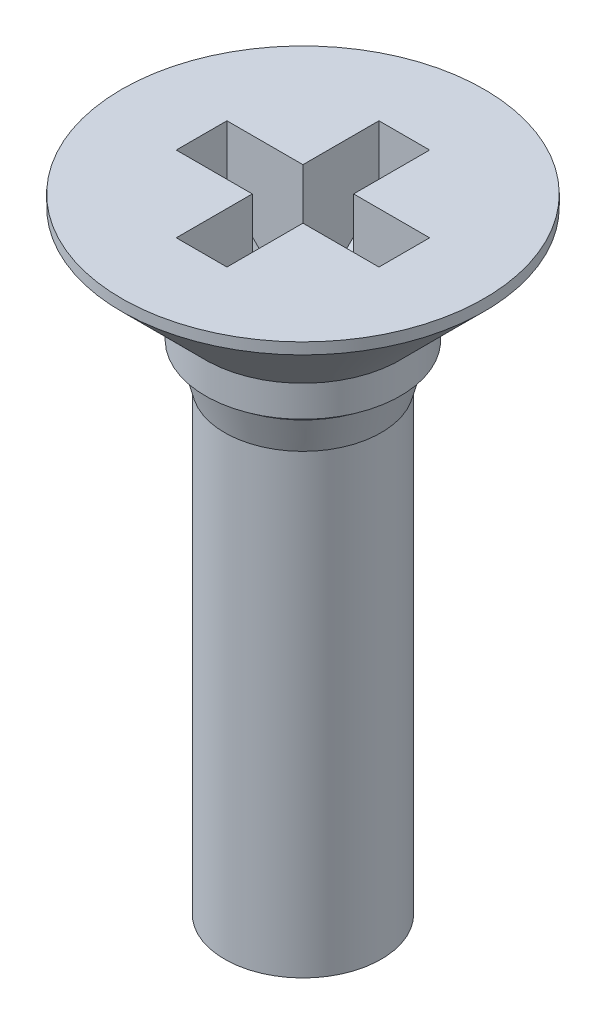
SolidWorks part; units mm, degrees
ref_plane "Vorderseite" through (0, 0, 0) normal (0, 0, 1) x (1, 0, 0)
ref_plane "Oben" through (0, 0, 0) normal (0, 1, 0) x (1, 0, 0)
ref_plane "Rechts" through (0, 0, 0) normal (1, 0, 0) x (0, 0, -1)
sketch "Skizze1" plane through (0, 0, 0) normal (0, 0, 1) x (1, 0, 0)
  line L0 (0, 0) -> (4.65, 0)
  line L1 (4.65, 0) -> (4.65, -0.29)
  line L2 (4.65, -0.29) -> (2.5, -2.44)
  line L3 (2.24, -3.24) -> (2.24, -3.4398)
  line L4 (2.24, -3.4398) -> (2.0095, -4.3)
  line L5 (2.0095, -4.3) -> (2.0095, -16)
  line L6 (2.0095, -16) -> (0, -16)
  line L7 (0, 0) -> (0, -16) construction
  line L8 (0, 0) -> (0, -16)
  line L10 (2.5, -2.44) -> (2.5, -3.24)
  line L12 (2.5, -3.24) -> (2.24, -3.24)
  point P3 (2.24, -2.7)
  dimension "D1" = 45
  dimension "D2" = 15
  dimension "K" = 2.7
  dimension "DA" = 9.3
  dimension "DK" = 4.019
  dimension "L" = 16
  dimension "DG" = 5
  dimension "A" = 1.6
  dimension "DF" = 4.48
  dimension "P" = 0.8
revolve "Basis-Rotation" add sketch "Skizze1" angle 360 about L7
sketch "Skizze2" plane through (0, 0, 0) normal (0, 0, 1) x (1, 0, 0)
  line L0 (0, -3.2) -> (0, 0) construction
  line L1 (0, 0) -> (0, -16) construction
  line L2 (-1, -3.2) -> (1, -3.2)
  line L3 (2.6, 0) -> (2.6, -1.6)
  line L4 (2.6, -1.6) -> (1, -3.2)
  line L5 (2.6, 0) -> (-2.6, 0)
  line L6 (-2.6, -1.6) -> (-1, -3.2)
  line L7 (-2.6, 0) -> (-2.6, -1.6)
  line L8 (0, -1.6) -> (2.6, -1.6) construction
  line L9 (4.65, 0) -> (-4.65, 0) construction
  line L11 (2.5, -2.44) -> (4.65, -0.29) construction
  point P11 (0, 0)
  dimension "M" = 5.2
  dimension "T" = 3.2
extrude "Kreuzschlitz1 H" cut sketch "Skizze2" against normal blind 0.65 and the other way blind 0.65
sketch "Skizze3" plane through (0, 0, 0) normal (1, 0, 0) x (0, 0, -1)
  line L0 (0, -3.2) -> (0, 0) construction
  line L2 (-1, -3.2) -> (1, -3.2)
  line L3 (2.6, 0) -> (2.6, -1.6)
  line L4 (2.6, -1.6) -> (1, -3.2)
  line L5 (2.6, 0) -> (-2.6, 0)
  line L6 (-2.6, -1.6) -> (-1, -3.2)
  line L7 (-2.6, 0) -> (-2.6, -1.6)
  line L8 (0, -1.6) -> (2.6, -1.6) construction
  point P11 (0, 0)
extrude "Kreuzschlitz2 H" cut sketch "Skizze3" against normal blind 0.65 and the other way blind 0.65
sketch "Skizze4" plane through (2.4522, 0, -1.8507) normal (0, 1, 0) x (-1, 0, 0)
  line L0 (7.3522, 1.8507) -> (-2.4478, 1.8507) construction
  line L1 (2.4522, -3.0493) -> (2.4522, 6.7507) construction
  line L2 (-2.4478, 1.0342) -> (-2.4478, 2.6672)
  line L3 (-2.4478, 1.0342) -> (0.0059, 1.0342)
  line L4 (0.0059, 1.0342) -> (0.8191, 0.6258)
  line L5 (1.2273, 0.2176) -> (-1.0126, -1.6141)
  line L6 (0.8191, 0.6258) -> (-1.0126, -1.6141)
  line L7 (1.6357, -0.5956) -> (1.2273, 0.2176)
  line L8 (1.6357, -3.0493) -> (1.6357, -0.5956)
  line L9 (1.6357, -3.0493) -> (3.2687, -3.0493)
  line L10 (3.2687, -3.0493) -> (3.2687, -0.5956)
  line L11 (3.2687, -0.5956) -> (3.6772, 0.2176)
  line L12 (2.4522, 1.8507) -> (-1.0126, -1.6141) construction
  line L13 (4.0854, 0.6258) -> (5.917, -1.6141)
  line L14 (3.6772, 0.2176) -> (5.917, -1.6141)
  line L15 (4.8986, 1.0342) -> (4.0854, 0.6258)
  line L16 (7.3522, 1.0342) -> (4.8986, 1.0342)
  line L17 (7.3522, 1.0342) -> (7.3522, 2.6672)
  line L18 (7.3522, 2.6672) -> (4.8986, 2.6672)
  line L19 (4.8986, 2.6672) -> (4.0854, 3.0757)
  line L20 (3.6772, 3.4839) -> (5.917, 5.3156)
  line L21 (4.0854, 3.0757) -> (5.917, 5.3156)
  line L22 (3.2687, 4.2971) -> (3.6772, 3.4839)
  line L23 (3.2687, 6.7507) -> (3.2687, 4.2971)
  line L24 (1.6357, 6.7507) -> (3.2687, 6.7507)
  line L25 (1.6357, 6.7507) -> (1.6357, 4.2971)
  line L26 (1.6357, 4.2971) -> (1.2273, 3.4839)
  line L27 (0.8191, 3.0757) -> (-1.0126, 5.3156)
  line L28 (1.2273, 3.4839) -> (-1.0126, 5.3156)
  line L29 (0.0059, 2.6672) -> (0.8191, 3.0757)
  line L30 (-2.4478, 2.6672) -> (0.0059, 2.6672)
  circle A0 centre (2.4522, 1.8507) radius 4.9 construction
  circle A1 centre (2.4522, 1.8507) radius 2.0415 construction
  circle A2 centre (2.4522, 1.8507) radius 2.579 construction
  dimension "X2" = 4.083
  dimension "X1" = 5.158
  dimension "M" = 9.8
  dimension "D3" = 5.725
  dimension "X3" = 1.633
